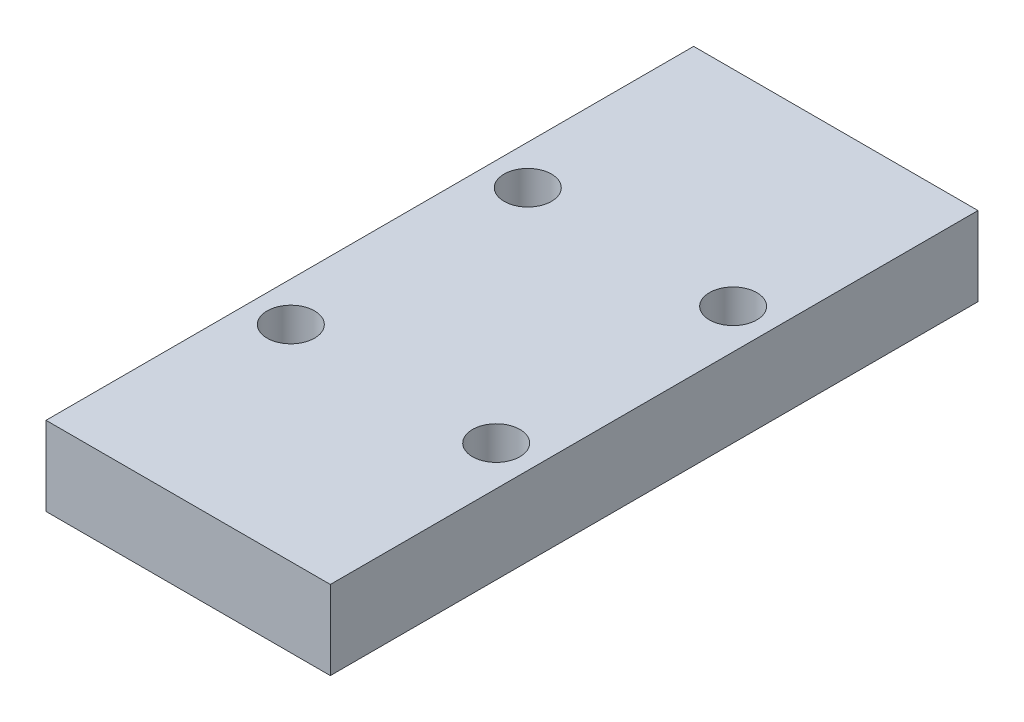
SolidWorks part; units mm, degrees
ref_plane "Front Plane" through (0, 0, 0) normal (0, 0, 1) x (1, 0, 0)
ref_plane "Top Plane" through (0, 0, 0) normal (0, 1, 0) x (1, 0, 0)
ref_plane "Right Plane" through (0, 0, 0) normal (1, 0, 0) x (0, 0, -1)
sketch "Sketch1" plane through (0, 0, 0) normal (0, 1, 0) x (1, 0, 0)
  line L1 (0, 0) -> (9, 0)
  line L2 (0, 0) -> (0, 41)
  line L3 (0, 41) -> (9, 41)
  line L4 (9, 0) -> (9, 41)
  circle A0 centre (2.5, 13) radius 1.5
  circle A1 centre (2.5, 28) radius 1.5
  dimension "D3" = 3
  dimension "D4" = 3
  dimension "D1" = 9
  dimension "D2" = 41
  dimension "D5" = 2.5
  dimension "D6" = 2.5
  dimension "D7" = 13
  dimension "D8" = 13
extrude "Boss-Extrude1" add sketch "Sketch1" along normal blind 5
mirror "Mirror1" about plane through (9, 5, 0) normal (-1, 0, 0) of "Boss-Extrude1"
